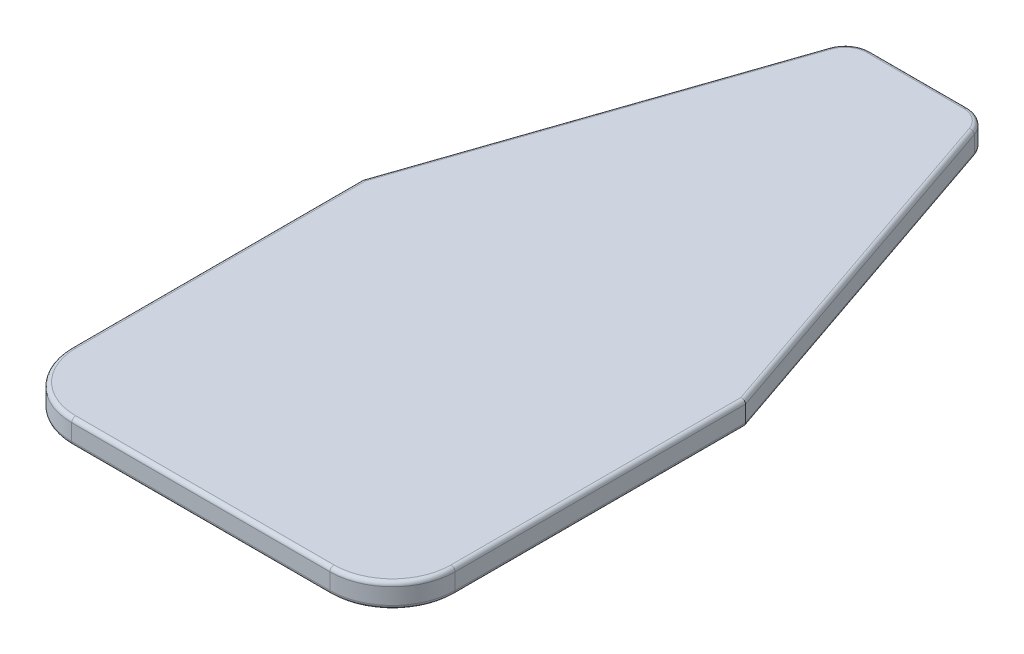
SolidWorks part; units mm, degrees
ref_plane "Front Plane" through (0, 0, 0) normal (0, 0, 1) x (1, 0, 0)
ref_plane "Top Plane" through (0, 0, 0) normal (0, 1, 0) x (1, 0, 0)
ref_plane "Right Plane" through (0, 0, 0) normal (1, 0, 0) x (0, 0, -1)
sketch "Sketch1" plane through (0, 0, 0) normal (0, 1, 0) x (1, 0, 0)
  line L0 (-101.6, -24.3645) -> (101.6, -24.3645)
  line L1 (-38.1, 540.7855) -> (38.1, 540.7855)
  line L2 (0, 540.7855) -> (0, -24.3645) construction
  line L3 (150.8125, 253.448) -> (57.15, 527.1697)
  line L4 (-150.8125, 253.448) -> (-57.15, 527.1697)
  line L5 (-150.8125, 253.448) -> (0, 253.448) construction
  line L6 (150.8125, 253.448) -> (0, 253.448) construction
  line L7 (-150.8125, 24.848) -> (-150.8125, 253.448)
  line L8 (150.8125, 24.848) -> (150.8125, 253.448)
  line L9 (-150.8125, 24.848) -> (0, 24.848) construction
  line L10 (150.8125, 24.848) -> (0, 24.848) construction
  arc A0 (101.6, -24.3645) -> (150.8125, 24.848) centre (101.6, 24.848) ccw
  arc A1 (-150.8125, 24.848) -> (-101.6, -24.3645) centre (-101.6, 24.848) ccw
  arc A2 (57.15, 527.1697) -> (38.1, 540.7855) centre (38.1, 520.6511) ccw
  arc A3 (-38.1, 540.7855) -> (-57.15, 527.1697) centre (-38.1, 520.6511) ccw
  dimension "D2" = 114.3
  dimension "D6" = 76.2
  dimension "D7" = 49.2125
  dimension "D8" = 20.1344
  dimension "D1" = 203.2
  dimension "D3" = 228.6
  dimension "D4" = 565.15
  dimension "D5" = 301.625
extrude "Boss-Extrude1" add sketch "Sketch1" along normal blind 19.05
fillet "Fillet1" radius 3.175 10 edges at (-103.9813, 19.05, -390.3089) (-49.8078, 19.05, -537.0316) (0, 19.05, -540.7855) (49.8078, 19.05, -537.0316) (-150.8125, 19.05, -139.148) (-136.3985, 19.05, 9.9505) (0, 19.05, 24.3645) (136.3985, 19.05, 9.9505) (103.9812, 19.05, -390.3089) (150.8125, 19.05, -139.148)
fillet "Fillet2" radius 3.175 10 edges at (103.9812, 0, -390.3089) (49.8078, 0, -537.0316) (0, 0, -540.7855) (-49.8078, 0, -537.0316) (-150.8125, 0, -139.148) (-136.3985, 0, 9.9505) (150.8125, 0, -139.148) (136.3985, 0, 9.9505) (-103.9813, 0, -390.3089) (0, 0, 24.3645)
sketch "Sketch5" plane through (0, 19.05, 0) normal (0, 1, 0) x (1, 0, 0)
  line L0 (38.1, 537.6105) -> (-38.1, 537.6105) construction
  line L1 (0, -21.1895) -> (-0.003, 542.4026) construction
  line L2 (-43.3215, 507.7584) -> (43.3215, 507.7584) construction
  line L3 (-101.6, -21.1895) -> (101.6, -21.1895) construction
  line L4 (43.3215, 507.7584) -> (60.4365, 507.7584) construction
  line L5 (147.6375, 252.9198) -> (54.146, 526.1418) construction
  line L6 (-43.3215, 507.7584) -> (-60.4365, 507.7584) construction
  line L7 (-54.146, 526.1418) -> (-147.6375, 252.9198) construction
  line B0 (-35.109, 447.4484) -> (35.2377, 518.3442) construction
  line B1 (-35.1059, 518.2113) -> (35.109, 447.4484) construction
  arc B2 (-24.9328, 526.498) -> (24.9268, 526.498) centre (-0.003, 542.4026) ccw
  arc B3 (-43.3215, 507.7584) -> (-24.9328, 526.498) centre (7.5558, 476.2258) cw
  arc B4 (24.9268, 526.498) -> (43.3215, 507.7584) centre (-2.6466, 481.0344) cw
  arc B5 (43.3215, 507.7584) -> (43.2864, 457.8401) centre (60.0594, 482.7875) ccw
  arc B6 (43.2864, 457.8401) -> (24.9269, 439.51) centre (-3.0428, 485.8841) cw
  arc B7 (-24.9914, 439.5451) -> (-43.2864, 457.8401) centre (3.0881, 485.9196) cw
  arc B8 (-43.3215, 507.7584) -> (-43.2864, 457.8401) centre (-60.0645, 482.7875) cw
  arc B9 (-24.9914, 439.5451) -> (24.9269, 439.51) centre (-0.0437, 423.2596) cw
  circle B10 centre (-30.052, 512.8835) radius 2.25
  circle B11 centre (30.0521, 512.8835) radius 2.25
  circle B12 centre (30.0519, 452.7794) radius 2.25
  circle B13 centre (-30.0527, 452.7791) radius 2.25
  circle B14 centre (0.0248, 482.837) radius 12.27
  line B15 (59.1543, -0.8785) -> (129.501, 70.0173) construction
  line B16 (59.1575, 69.8844) -> (129.3724, -0.8785) construction
  arc B17 (69.3306, 78.1711) -> (119.1902, 78.1711) centre (94.2604, 94.0757) ccw
  arc B18 (50.9418, 59.4315) -> (69.3306, 78.1711) centre (101.8192, 27.8988) cw
  arc B19 (119.1902, 78.1711) -> (137.5848, 59.4315) centre (91.6168, 32.7074) cw
  arc B20 (137.5848, 59.4315) -> (137.5497, 9.5132) centre (154.3228, 34.4605) ccw
  arc B21 (137.5497, 9.5132) -> (119.1902, -8.8169) centre (91.2205, 37.5572) cw
  arc B22 (69.2719, -8.7818) -> (50.9769, 9.5132) centre (97.3515, 37.5927) cw
  arc B23 (50.9418, 59.4315) -> (50.9769, 9.5132) centre (34.1989, 34.4605) cw
  arc B24 (69.2719, -8.7818) -> (119.1902, -8.8169) centre (94.2197, -25.0673) cw
  circle B25 centre (64.2114, 64.5566) radius 2.25
  circle B26 centre (124.3154, 64.5566) radius 2.25
  circle B27 centre (124.3152, 4.4525) radius 2.25
  circle B28 centre (64.2106, 4.4522) radius 2.25
  circle B29 centre (94.2881, 34.5101) radius 12.27
  line B30 (-59.1545, -0.8791) -> (-129.502, 70.0159) construction
  line B31 (-59.1584, 69.8838) -> (-129.3726, -0.8798) construction
  arc B32 (-69.3316, 78.1704) -> (-119.1912, 78.1699) centre (-94.2616, 94.0747) cw
  arc B33 (-50.9427, 59.4309) -> (-69.3316, 78.1704) centre (-101.8197, 27.8978) ccw
  arc B34 (-119.1912, 78.1699) -> (-137.5857, 59.43) centre (-91.6173, 32.7065) ccw
  arc B35 (-137.5857, 59.43) -> (-137.5501, 9.5117) centre (-154.3234, 34.4589) cw
  arc B36 (-137.5501, 9.5117) -> (-119.1904, -8.8182) centre (-91.2211, 37.5562) ccw
  arc B37 (-69.2721, -8.7826) -> (-50.9773, 9.5126) centre (-97.3521, 37.5917) ccw
  arc B38 (-50.9427, 59.4309) -> (-50.9773, 9.5126) centre (-34.1994, 34.4602) ccw
  arc B39 (-69.2721, -8.7826) -> (-119.1904, -8.8182) centre (-94.2196, -25.0683) ccw
  circle B40 centre (-64.2123, 64.5559) radius 2.25
  circle B41 centre (-124.3163, 64.5553) radius 2.25
  circle B42 centre (-124.3155, 4.4512) radius 2.25
  circle B43 centre (-64.2109, 4.4515) radius 2.25
  circle B44 centre (-94.2887, 34.5091) radius 12.27
  line B45 (144.3193, 78.0251) -> (128.3193, 78.0251)
  line B46 (144.3193, 78.0251) -> (144.3193, 168.0251)
  line B47 (128.3193, 78.0251) -> (128.3193, 168.0251)
  circle B48 centre (136.3192, 84.2751) radius 2.25
  circle B49 centre (136.3192, 161.7751) radius 2.25
  line B50 (-144.3203, 78.0236) -> (-128.3203, 78.0237)
  line B51 (-144.3203, 78.0236) -> (-144.3212, 168.0236)
  line B52 (-128.3203, 78.0237) -> (-128.3212, 168.0237)
  circle B53 centre (-136.3203, 84.2736) radius 2.25
  circle B54 centre (-136.3211, 161.7737) radius 2.25
  dimension "D1" = 11.1125
  dimension "D2" = 11.1125
sketch_block_instance "Block2-1"
sketch_block "Block2"
sketch_block_instance "Block2-6"
sketch_block_instance "Block2-7"
sketch_block_instance "Block1-1"
sketch_block "Block1"
sketch_block_instance "Block1-2"
